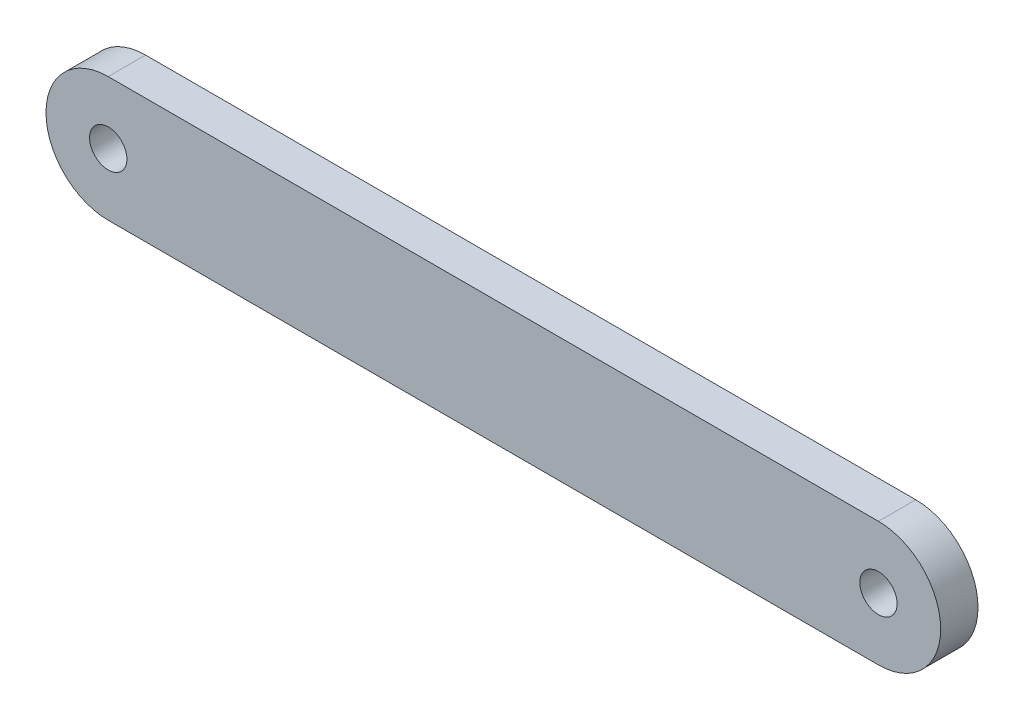
SolidWorks part; units mm, degrees
material "Acrylic (Medium-high impact)"
ref_plane "Front Plane" through (0, 0, 0) normal (0, 0, 1) x (1, 0, 0)
ref_plane "Top Plane" through (0, 0, 0) normal (0, 1, 0) x (1, 0, 0)
ref_plane "Right Plane" through (0, 0, 0) normal (1, 0, 0) x (0, 0, -1)
sketch "Sketch1" plane through (0, 0, 0) normal (0, 0, 1) x (1, 0, 0)
  line L0 (0, 0) -> (61.9, 0) construction
  line L1 (0, 5) -> (61.9, 5)
  line L2 (0, -5) -> (61.9, -5)
  arc A0 (0, 5) -> (0, -5) centre (0, 0) ccw
  arc A1 (61.9, -5) -> (61.9, 5) centre (61.9, 0) ccw
  circle A2 centre (0, 0) radius 1.5
  circle A3 centre (61.9, 0) radius 1.5
  point P3 (30.95, 0)
  dimension "D3" = 3
  dimension "D4" = 3
  dimension "D1" = 61.9
  dimension "D2" = 10
extrude "Boss-Extrude1" add sketch "Sketch1" along normal blind 3
